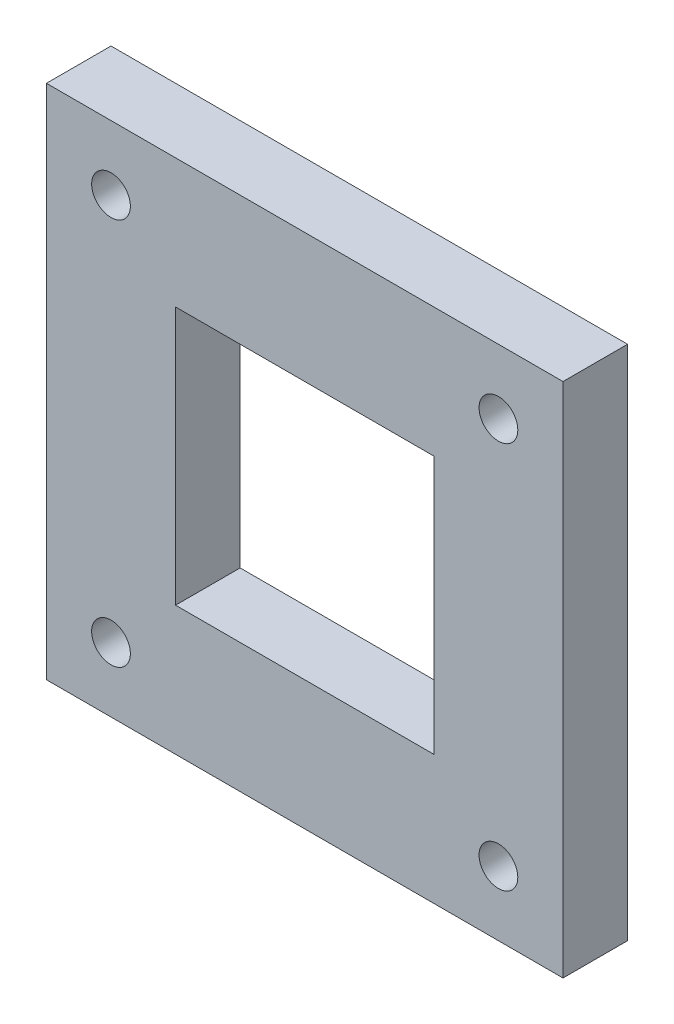
SolidWorks part; units mm, degrees
ref_plane "Plano frontal" through (0, 0, 0) normal (0, 0, 1) x (1, 0, 0)
ref_plane "Plano superior" through (0, 0, 0) normal (0, 1, 0) x (1, 0, 0)
ref_plane "Plano direito" through (0, 0, 0) normal (1, 0, 0) x (0, 0, -1)
sketch "Esboço1" plane through (0, 0, 0) normal (0, 0, 1) x (1, 0, 0)
  line L1 (20, 0) -> (20, 20)
  line L2 (20, 20) -> (-20, 20)
  line L3 (-20, 20) -> (-20, -20)
  line L4 (-20, -20) -> (20, -20)
  line L6 (20, -20) -> (20, 0)
  point P0 (0, 0)
  point P2 (0, 0)
extrude "Ressalto-extrusão1" add sketch "Esboço1" along normal blind 5 contours L1 L2 L3 L4 L6
sketch "Esboço2" plane through (0, 0, 5) normal (0, 0, 1) x (1, 0, 0)
  line L1 (10, 10) -> (10, -10)
  line L3 (10, 10) -> (-10, 10)
  line L19 (-10, -10) -> (-10, 10)
  line L20 (-10, -10) -> (10, -10)
  circle A0 centre (-15, 15) radius 1.5
  circle A1 centre (15, 15) radius 1.5
  circle A2 centre (-15, -15) radius 1.5
  circle A3 centre (15, -15) radius 1.5
extrude "Corte-extrusão1" cut sketch "Esboço2" against normal through all
